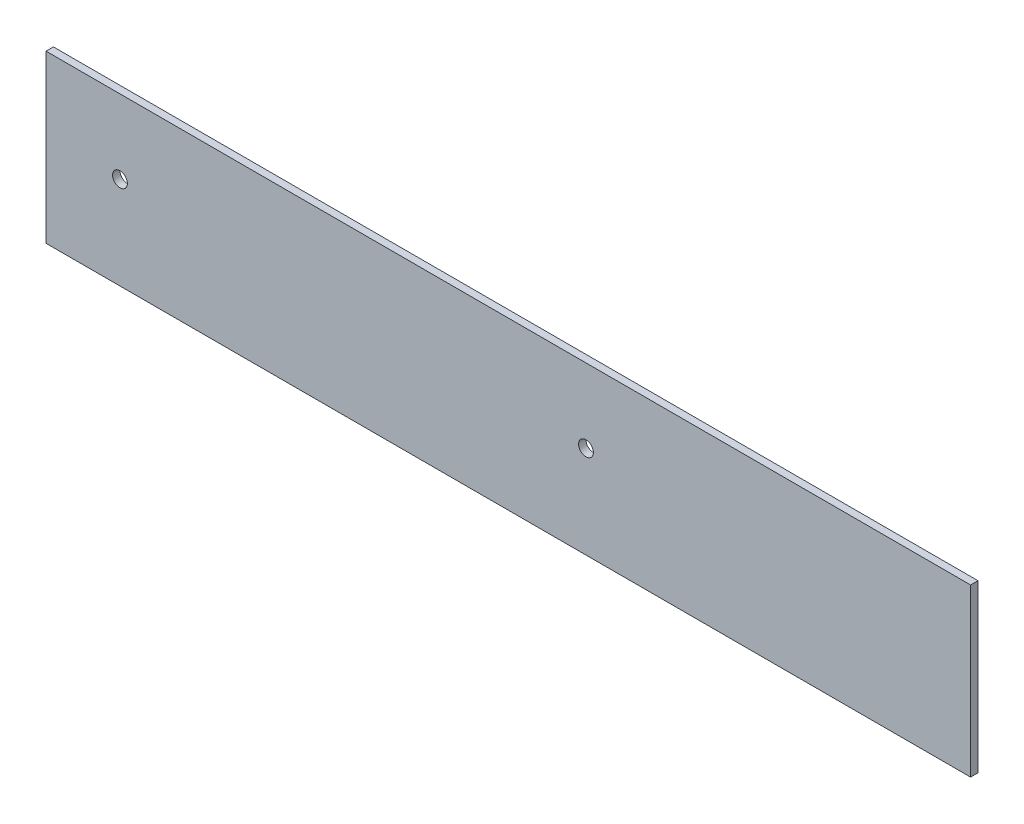
SolidWorks part; units mm, degrees
ref_plane "Front Plane" through (0, 0, 0) normal (0, 0, 1) x (1, 0, 0)
ref_plane "Top Plane" through (0, 0, 0) normal (0, 1, 0) x (1, 0, 0)
ref_plane "Right Plane" through (0, 0, 0) normal (1, 0, 0) x (0, 0, -1)
sketch "Sketch1" plane through (0, 0, 0) normal (0, 0, 1) x (1, 0, 0)
  line L1 (-125, 22.5) -> (125, 22.5)
  line L2 (-125, 22.5) -> (-125, -22.5)
  line L3 (-125, -22.5) -> (125, -22.5)
  line L4 (125, 22.5) -> (125, -22.5)
  line L5 (-125, 22.5) -> (125, -22.5) construction
  line L6 (-125, -22.5) -> (125, 22.5) construction
  point P0 (0, 0)
  dimension "D1" = 45
  dimension "D2" = 250
extrude "Boss-Extrude1" add sketch "Sketch1" along normal blind 2
sketch "Sketch2" plane through (0, 0, 0) normal (0, 0, 1) x (1, 0, 0)
  line L0 (-125, 22.5) -> (-125, -22.5) construction
  line L1 (125, -22.5) -> (125, 22.5) construction
  line L2 (-125, -22.5) -> (125, -22.5) construction
  circle A0 centre (-105, 2.5) radius 2
  circle A1 centre (21, 2.5) radius 2
  dimension "D1" = 4
  dimension "D2" = 4
  dimension "D3" = 20
  dimension "D4" = 104
  dimension "D5" = 25
  dimension "D6" = 25
extrude "Cut-Extrude2" cut sketch "Sketch2" against normal blind 2 and the other way through all
